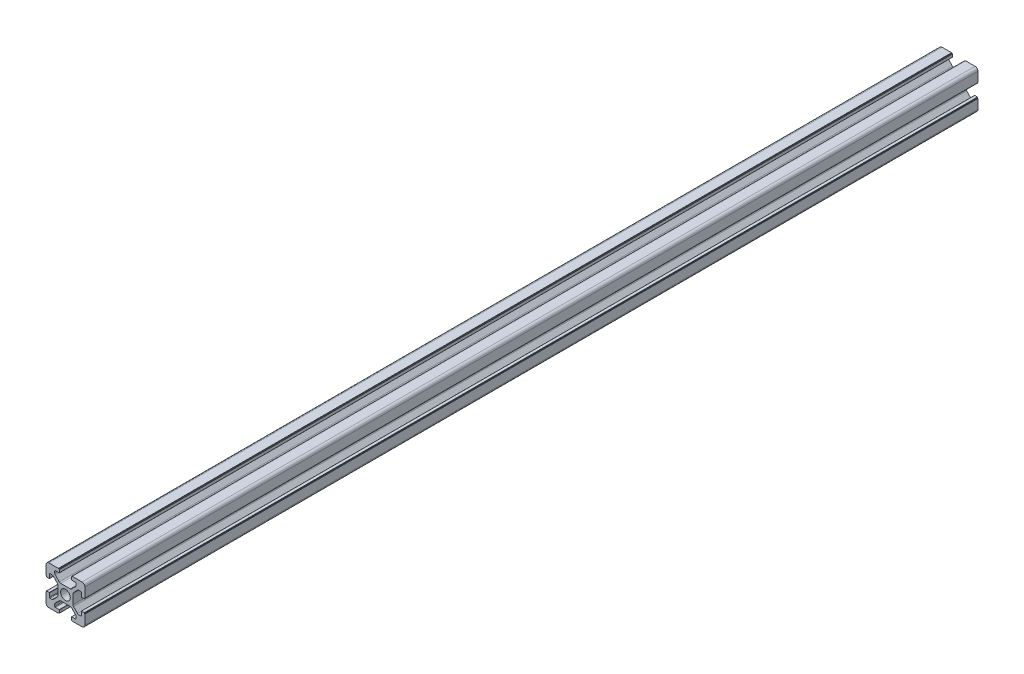
SolidWorks part; units mm, degrees
material "6063-T5"
ref_plane "前视基准面" through (0, 0, 0) normal (0, 0, 1) x (1, 0, 0)
ref_plane "上视基准面" through (0, 0, 0) normal (0, 1, 0) x (1, 0, 0)
ref_plane "右视基准面" through (0, 0, 0) normal (1, 0, 0) x (0, 0, -1)
sketch "草图1" plane through (0, 0, 0) normal (0, 0, 1) x (1, 0, 0)
  line L0 (-1.4389, 10) -> (24.3741, 10) construction
  line L1 (20, 13.6) -> (20, 20)
  line L2 (0, 0) -> (0, 6.4)
  line L3 (0, 20) -> (6.4, 20)
  line L4 (20, 0) -> (20, 6.4)
  line L5 (10, 21.5388) -> (10, -2.4017) construction
  line L6 (6.9, 18.3) -> (6.9, 19.7)
  line L7 (6.8, 18.2) -> (4.8, 18.2)
  line L8 (4.5, 17.9) -> (4.5, 16.9749)
  line L9 (4.7929, 16.2678) -> (6.8678, 14.1929)
  line L10 (7.5749, 13.9) -> (12.4251, 13.9)
  line L11 (6.8, 19.8) -> (6.4, 19.8)
  line L12 (6.4, 19.8) -> (6.4, 20)
  line L13 (0, 13.6) -> (0.2, 13.6)
  line L14 (0.2, 13.6) -> (0.2, 13.2)
  line L15 (0.3, 13.1) -> (1.7, 13.1)
  line L16 (1.8, 13.2) -> (1.8, 15.2)
  line L17 (2.1, 15.5) -> (3.0251, 15.5)
  line L18 (3.7322, 15.2071) -> (5.8071, 13.1322)
  line L19 (6.1, 12.4251) -> (6.1, 7.5749)
  line L20 (13.6, 19.8) -> (13.6, 20)
  line L21 (13.2, 19.8) -> (13.6, 19.8)
  line L22 (13.1, 18.3) -> (13.1, 19.7)
  line L23 (13.2, 18.2) -> (15.2, 18.2)
  line L24 (15.5, 17.9) -> (15.5, 16.9749)
  line L25 (15.2071, 16.2678) -> (13.1322, 14.1929)
  line L26 (0, 6.4) -> (0.2, 6.4)
  line L27 (0.2, 6.4) -> (0.2, 6.8)
  line L28 (0.3, 6.9) -> (1.7, 6.9)
  line L29 (1.8, 6.8) -> (1.8, 4.8)
  line L30 (2.1, 4.5) -> (3.0251, 4.5)
  line L31 (3.7322, 4.7929) -> (5.8071, 6.8678)
  line L32 (13.6, 20) -> (20, 20)
  line L33 (0, 13.6) -> (0, 20)
  line L34 (13.6, 0.2) -> (13.6, 0)
  line L35 (13.2, 0.2) -> (13.6, 0.2)
  line L36 (13.1, 1.7) -> (13.1, 0.3)
  line L37 (13.2, 1.8) -> (15.2, 1.8)
  line L38 (15.5, 2.1) -> (15.5, 3.0251)
  line L39 (15.2071, 3.7322) -> (13.1322, 5.8071)
  line L40 (4.5, 2.1) -> (4.5, 3.0251)
  line L41 (6.8, 1.8) -> (4.8, 1.8)
  line L42 (6.4, 0.2) -> (6.4, 0)
  line L43 (6.8, 0.2) -> (6.4, 0.2)
  line L44 (6.9, 1.7) -> (6.9, 0.3)
  line L45 (4.7929, 3.7322) -> (6.8678, 5.8071)
  line L46 (7.5749, 6.1) -> (12.4251, 6.1)
  line L47 (20, 6.4) -> (19.8, 6.4)
  line L48 (19.8, 6.4) -> (19.8, 6.8)
  line L49 (19.7, 6.9) -> (18.3, 6.9)
  line L50 (18.2, 6.8) -> (18.2, 4.8)
  line L51 (17.9, 4.5) -> (16.9749, 4.5)
  line L52 (16.2678, 4.7929) -> (14.1929, 6.8678)
  line L53 (13.9, 12.4251) -> (13.9, 7.5749)
  line L54 (16.2678, 15.2071) -> (14.1929, 13.1322)
  line L55 (17.9, 15.5) -> (16.9749, 15.5)
  line L56 (18.2, 13.2) -> (18.2, 15.2)
  line L57 (19.7, 13.1) -> (18.3, 13.1)
  line L58 (19.8, 13.6) -> (19.8, 13.2)
  line L59 (20, 13.6) -> (19.8, 13.6)
  line L60 (0, 0) -> (6.4, 0)
  line L61 (13.6, 0) -> (20, 0)
  arc A0 (6.1, 12.4251) -> (5.8071, 13.1322) centre (5.1, 12.4251) ccw
  arc A1 (7.5749, 13.9) -> (6.8678, 14.1929) centre (7.5749, 14.9) cw
  arc A2 (4.5, 16.9749) -> (4.7929, 16.2678) centre (5.5, 16.9749) ccw
  arc A3 (3.7322, 15.2071) -> (3.0251, 15.5) centre (3.0251, 14.5) ccw
  arc A4 (4.5, 17.9) -> (4.8, 18.2) centre (4.8, 17.9) cw
  arc A5 (1.8, 15.2) -> (2.1, 15.5) centre (2.1, 15.2) cw
  arc A6 (0.3, 13.1) -> (0.2, 13.2) centre (0.3, 13.2) cw
  arc A7 (6.9, 19.7) -> (6.8, 19.8) centre (6.8, 19.7) ccw
  arc A8 (1.7, 13.1) -> (1.8, 13.2) centre (1.7, 13.2) ccw
  arc A9 (6.9, 18.3) -> (6.8, 18.2) centre (6.8, 18.3) cw
  arc A10 (13.1, 19.7) -> (13.2, 19.8) centre (13.2, 19.7) cw
  arc A11 (13.1, 18.3) -> (13.2, 18.2) centre (13.2, 18.3) ccw
  arc A12 (15.5, 17.9) -> (15.2, 18.2) centre (15.2, 17.9) ccw
  arc A13 (15.5, 16.9749) -> (15.2071, 16.2678) centre (14.5, 16.9749) cw
  arc A14 (12.4251, 13.9) -> (13.1322, 14.1929) centre (12.4251, 14.9) ccw
  arc A15 (0.3, 6.9) -> (0.2, 6.8) centre (0.3, 6.8) ccw
  arc A16 (1.7, 6.9) -> (1.8, 6.8) centre (1.7, 6.8) cw
  arc A17 (1.8, 4.8) -> (2.1, 4.5) centre (2.1, 4.8) ccw
  arc A18 (3.7322, 4.7929) -> (3.0251, 4.5) centre (3.0251, 5.5) cw
  arc A19 (6.1, 7.5749) -> (5.8071, 6.8678) centre (5.1, 7.5749) cw
  arc A20 (13.1, 0.3) -> (13.2, 0.2) centre (13.2, 0.3) ccw
  arc A21 (13.1, 1.7) -> (13.2, 1.8) centre (13.2, 1.7) cw
  arc A22 (15.5, 2.1) -> (15.2, 1.8) centre (15.2, 2.1) cw
  arc A23 (15.5, 3.0251) -> (15.2071, 3.7322) centre (14.5, 3.0251) ccw
  arc A24 (12.4251, 6.1) -> (13.1322, 5.8071) centre (12.4251, 5.1) cw
  arc A25 (4.5, 2.1) -> (4.8, 1.8) centre (4.8, 2.1) ccw
  arc A26 (6.9, 0.3) -> (6.8, 0.2) centre (6.8, 0.3) cw
  arc A27 (6.9, 1.7) -> (6.8, 1.8) centre (6.8, 1.7) ccw
  arc A28 (4.5, 3.0251) -> (4.7929, 3.7322) centre (5.5, 3.0251) cw
  arc A29 (7.5749, 6.1) -> (6.8678, 5.8071) centre (7.5749, 5.1) ccw
  arc A30 (19.7, 6.9) -> (19.8, 6.8) centre (19.7, 6.8) cw
  arc A31 (18.3, 6.9) -> (18.2, 6.8) centre (18.3, 6.8) ccw
  arc A32 (18.2, 4.8) -> (17.9, 4.5) centre (17.9, 4.8) cw
  arc A33 (16.2678, 4.7929) -> (16.9749, 4.5) centre (16.9749, 5.5) ccw
  arc A34 (13.9, 7.5749) -> (14.1929, 6.8678) centre (14.9, 7.5749) ccw
  arc A35 (13.9, 12.4251) -> (14.1929, 13.1322) centre (14.9, 12.4251) cw
  arc A36 (16.2678, 15.2071) -> (16.9749, 15.5) centre (16.9749, 14.5) cw
  arc A37 (18.2, 15.2) -> (17.9, 15.5) centre (17.9, 15.2) ccw
  arc A38 (18.3, 13.1) -> (18.2, 13.2) centre (18.3, 13.2) cw
  arc A39 (19.7, 13.1) -> (19.8, 13.2) centre (19.7, 13.2) ccw
  circle A40 centre (10, 10) radius 2.5
  point P39 (0.2, 13.1)
  point P42 (6.9, 19.8)
  point P45 (1.8, 13.1)
  point P48 (6.9, 18.2)
  point P66 (10, 13.9)
  point P83 (6.1, 10)
  dimension "D19" = 1
  dimension "D20" = 1
  dimension "D21" = 0.3
  dimension "D22" = 0.1
  dimension "D23" = 5
  dimension "D1" = 20
  dimension "D2" = 20
  dimension "D3" = 10
  dimension "D4" = 10
  dimension "D5" = 1.8
  dimension "D6" = 0.5
  dimension "D7" = 1.6
  dimension "D8" = 3.1
  dimension "D9" = 6.1
  dimension "D10" = 5.5
  dimension "D11" = 3.1
  dimension "D12" = 6.1
  dimension "D13" = 5.5
  dimension "D14" = 1.8
  dimension "D15" = 0.5
  dimension "D16" = 1.5
  dimension "D17" = 45
  dimension "D18" = 1.6
extrude "凸台-拉伸1" add sketch "草图1" along normal blind 460
fillet "圆角1" radius 1.5 4 edges at (20, 0, 230) (0, 0, 230) (0, 20, 230) (20, 20, 230)
